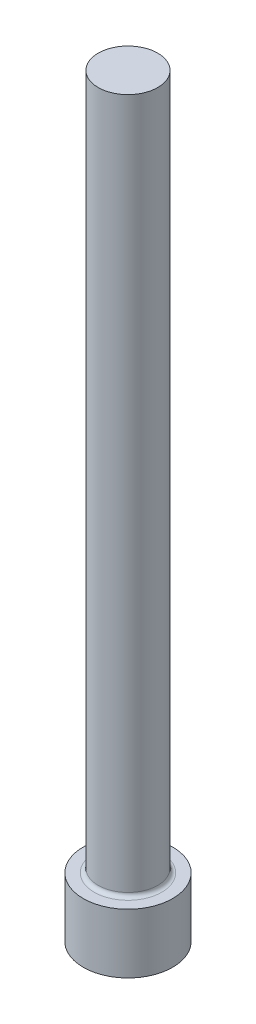
SolidWorks part; units mm, degrees
material "1023 碳钢板 (SS)"
ref_plane "前视基准面" through (0, 0, 0) normal (0, 0, 1) x (1, 0, 0)
ref_plane "上视基准面" through (0, 0, 0) normal (0, 1, 0) x (1, 0, 0)
ref_plane "右视基准面" through (0, 0, 0) normal (1, 0, 0) x (0, 0, -1)
sketch "草图1" plane through (0, 0, 0) normal (1, 0, 0) x (0, 0, -1)
  line L0 (0, 0) -> (-2.25, 0)
  line L1 (-2.25, 0) -> (-2.25, 3)
  line L2 (-2.25, 3) -> (-1.5, 3)
  line L3 (-1.5, 3) -> (-1.5, 38)
  line L4 (-1.5, 38) -> (0, 38)
  line L5 (0, 38) -> (0, 0)
  dimension "D1" = 1.5
  dimension "D2" = 2.25
  dimension "D3" = 3
  dimension "D4" = 35
revolve "旋转1" add sketch "草图1" angle 360 about L5
cosmetic thread "装饰螺纹线1" parameters "D2"=2.459
fillet "圆角1" radius 0.2 1 edges at (0, 3, 1.5)
sketch "草图2" plane through (0, 0, 0) normal (0, -1, 0) x (1, 0, 0)
  line L0 (0, 1.351) -> (-1.17, 0.6755)
  line L1 (-1.17, 0.6755) -> (-1.17, -0.6755)
  line L2 (-1.17, -0.6755) -> (0, -1.351)
  line L3 (0, -1.351) -> (1.17, -0.6755)
  line L4 (1.17, -0.6755) -> (1.17, 0.6755)
  line L5 (1.17, 0.6755) -> (0, 1.351)
  circle A0 centre (0, 0) radius 1.351 construction
  dimension "D1" = 2.34
extrude "切除-拉伸1" cut sketch "草图2" against normal blind 1.5
